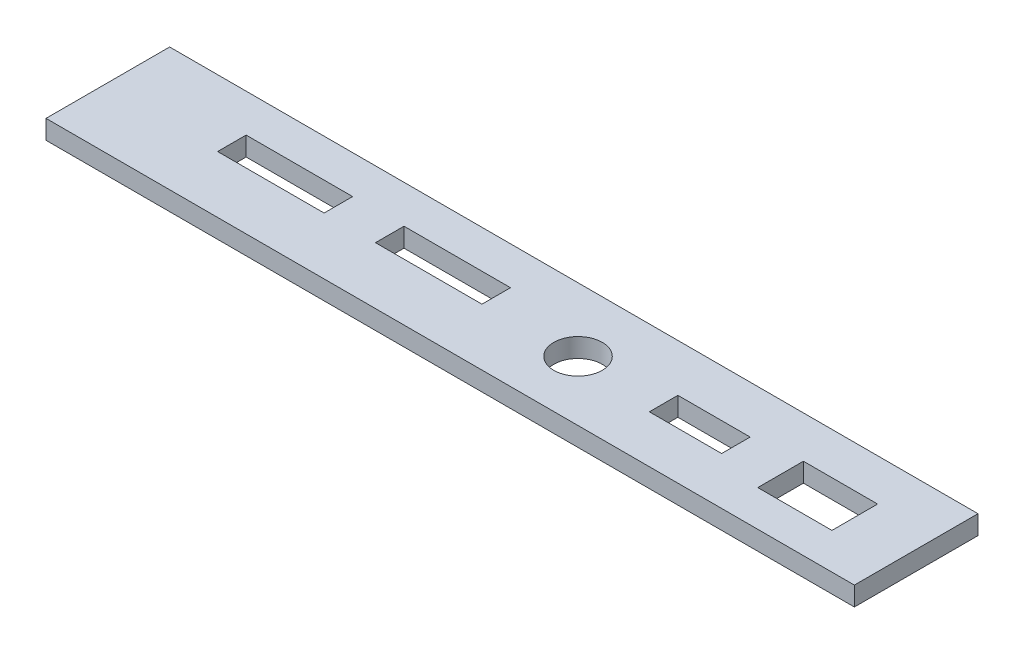
SolidWorks part; units mm, degrees
ref_plane "前视基准面" through (0, 0, 0) normal (0, 0, 1) x (1, 0, 0)
ref_plane "上视基准面" through (0, 0, 0) normal (0, 1, 0) x (1, 0, 0)
ref_plane "右视基准面" through (0, 0, 0) normal (1, 0, 0) x (0, 0, -1)
sketch "草图1" plane through (0, 0, 0) normal (0, 1, 0) x (1, 0, 0)
  line L0 (-10.0514, -3.1688) -> (74.9486, -3.1688) construction
  line L1 (-10.0514, 4.8312) -> (74.9486, 4.8312)
  line L2 (-10.0514, 4.8312) -> (-10.0514, -8.1688)
  line L3 (-10.0514, -8.1688) -> (74.9486, -8.1688)
  line L4 (74.9486, 4.8312) -> (74.9486, -8.1688)
  line L6 (68.7913, -4.3688) -> (60.9913, -4.3688)
  line L7 (68.7913, -4.3688) -> (68.7913, 0.4312)
  line L8 (68.7913, 0.4312) -> (60.9913, 0.4312)
  line L9 (60.9913, -4.3688) -> (60.9913, 0.4312)
  line L10 (68.7913, -4.3688) -> (60.9913, 0.4312) construction
  line L11 (68.7913, 0.4312) -> (60.9913, -4.3688) construction
  line L12 (55.9913, -3.1688) -> (48.3913, -3.1688)
  line L13 (55.9913, -3.1688) -> (55.9913, -0.1688)
  line L14 (55.9913, -0.1688) -> (48.3913, -0.1688)
  line L15 (48.3913, -3.1688) -> (48.3913, -0.1688)
  line L16 (55.9913, -3.1688) -> (48.3913, -0.1688) construction
  line L17 (55.9913, -0.1688) -> (48.3913, -3.1688) construction
  line L18 (29.7913, -2.1688) -> (18.5913, -2.1688)
  line L19 (29.7913, -2.1688) -> (29.7913, 0.8312)
  line L20 (29.7913, 0.8312) -> (18.5913, 0.8312)
  line L21 (18.5913, -2.1688) -> (18.5913, 0.8312)
  line L22 (29.7913, -2.1688) -> (18.5913, 0.8312) construction
  line L23 (29.7913, 0.8312) -> (18.5913, -2.1688) construction
  line L28 (1.9913, 0.8312) -> (13.1913, 0.8312)
  line L29 (1.9913, 0.8312) -> (1.9913, -2.1688)
  line L30 (1.9913, -2.1688) -> (13.1913, -2.1688)
  line L31 (13.1913, 0.8312) -> (13.1913, -2.1688)
  line L32 (1.9913, 0.8312) -> (13.1913, -2.1688) construction
  line L33 (1.9913, -2.1688) -> (13.1913, 0.8312) construction
  circle A0 centre (39.5913, -1.8688) radius 2.55
  point P4 (32.4486, 0.1541)
  point P11 (64.8913, -1.9688)
  point P16 (52.1913, -1.6688)
  point P19 (29.7913, -0.6688)
  point P24 (24.1913, -0.6688)
  point P29 (7.5913, -2.0287)
  point P42 (7.5913, -0.6688)
  dimension "D10" = 8.8
  dimension "D11" = 1.3
  dimension "D18" = 1
  dimension "D1" = 13
  dimension "D2" = 85
  dimension "D3" = 8
  dimension "D4" = 7.8
  dimension "D5" = 4.8
  dimension "D6" = 5
  dimension "D7" = 3
  dimension "D8" = 1.2
  dimension "D9" = 7.6
  dimension "D12" = 9.8
  dimension "D13" = 11.2
  dimension "D14" = 3
  dimension "D15" = 5.4
  dimension "D16" = 11.2
  dimension "D17" = 3
  dimension "D19" = 1
extrude "凸台-拉伸2" add sketch "草图1" along normal blind 2
